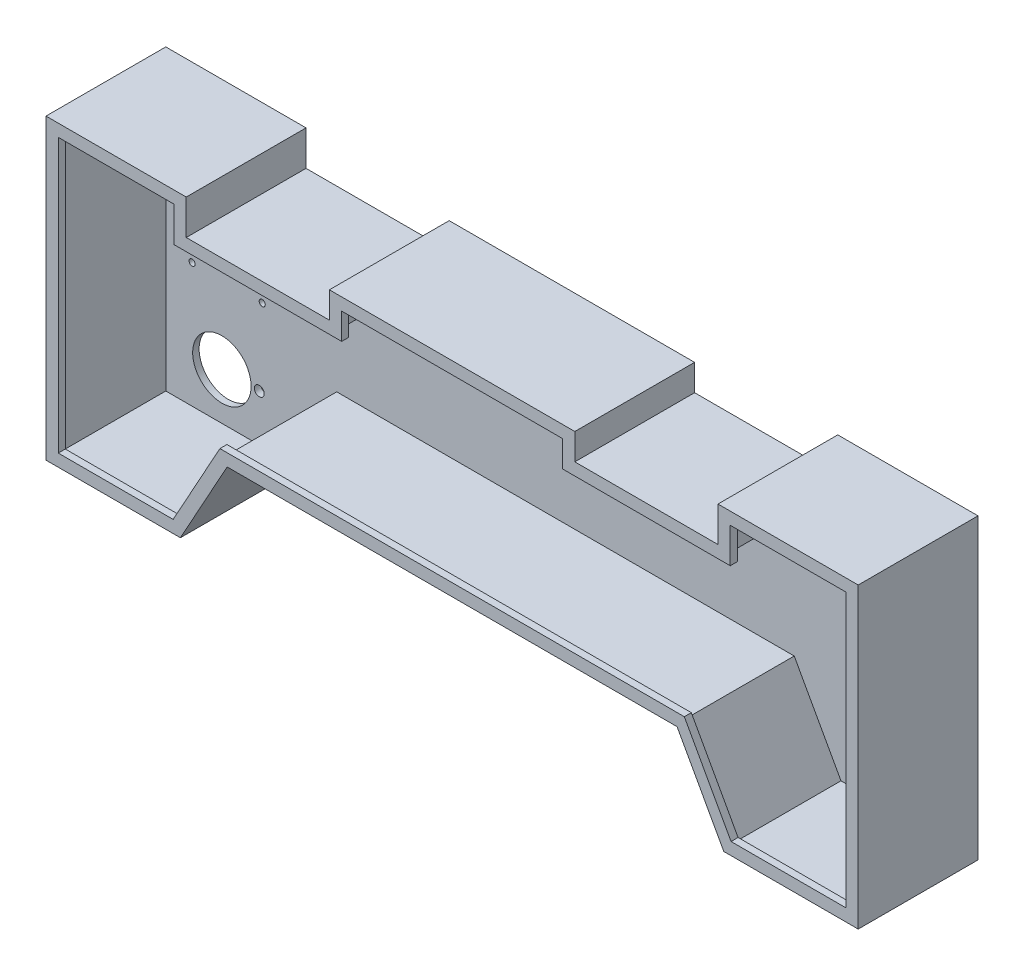
SolidWorks part; units mm, degrees
ref_plane "前视基准面" through (0, 0, 0) normal (0, 0, 1) x (1, 0, 0)
ref_plane "上视基准面" through (0, 0, 0) normal (0, 1, 0) x (1, 0, 0)
ref_plane "右视基准面" through (0, 0, 0) normal (1, 0, 0) x (0, 0, -1)
sketch "草图1" plane through (0, 0, 0) normal (0, 0, 1) x (1, 0, 0)
  line L0 (-61.0703, 36.5) -> (-37.0703, 36.5)
  line L1 (-37.0703, 36.5) -> (-37.0703, 30.5)
  line L2 (-37.0703, 30.5) -> (-12.5703, 30.5)
  line L3 (-12.5703, 30.5) -> (-12.5703, 35)
  line L4 (-12.5703, 35) -> (29.4297, 35)
  line L5 (29.4297, 35) -> (29.4297, 30.5)
  line L6 (29.4297, 30.5) -> (53.9297, 30.5)
  line L7 (53.9297, 30.5) -> (53.9297, 36.5)
  line L8 (53.9297, 36.5) -> (77.9297, 36.5)
  line L9 (77.9297, 36.5) -> (77.9297, -14.5)
  line L10 (77.9297, -14.5) -> (54.9297, -14.5)
  line L11 (-61.0703, 36.5) -> (-61.0703, -14.5)
  line L12 (-61.0703, -14.5) -> (-38.0703, -14.5)
  line L13 (8.4297, 98.6015) -> (8.4297, -28.6015) construction
  line L14 (-30.0703, 0) -> (46.9297, 0)
  line L15 (-30.0703, 0) -> (-38.0703, -14.5)
  line L16 (46.9297, 0) -> (54.9297, -14.5)
  point P17 (8.4297, 35)
  dimension "D1" = 24
  dimension "D2" = 6
  dimension "D3" = 24.5
  dimension "D4" = 4.5
  dimension "D5" = 42
  dimension "D6" = 4.5
  dimension "D7" = 24.5
  dimension "D8" = 6
  dimension "D9" = 24
  dimension "D10" = 51
  dimension "D11" = 51
  dimension "D12" = 77
  dimension "D13" = 38.5
  dimension "D14" = 30.5
  dimension "D15" = 23
  dimension "D16" = 23
extrude "凸台-拉伸1" add sketch "草图1" along normal blind 20.5
scale "缩放比例1" bodies to scale 106 scale about centroid uniform scaling yes scale factor 10
shell "抽壳1" thickness 11
ref_plane "基准面2" through (-457.5703, 231.1082, 112.75) normal (-1, 0, 0) x (0, 0, 1)
sketch "草图12" plane through (0, 0, 112.75) normal (0, 0, 1) x (1, 0, 0)
  line L32 (-665.5703, 221.1082) -> (-665.5703, -246.8918)
  line L33 (-665.5703, -246.8918) -> (-468.9682, -246.8918)
  line L34 (-468.9682, -246.8918) -> (-388.9682, -101.8918)
  line L35 (-388.9682, -101.8918) -> (405.8277, -101.8918)
  line L36 (405.8277, -101.8918) -> (485.8277, -246.8918)
  line L37 (485.8277, -246.8918) -> (682.4297, -246.8918)
  line L38 (682.4297, -246.8918) -> (682.4297, 221.1082)
  line L39 (682.4297, 221.1082) -> (484.4297, 221.1082)
  line L40 (484.4297, 221.1082) -> (484.4297, 161.1082)
  line L41 (484.4297, 161.1082) -> (197.4297, 161.1082)
  line L42 (197.4297, 161.1082) -> (197.4297, 206.1082)
  line L43 (197.4297, 206.1082) -> (-180.5703, 206.1082)
  line L44 (-180.5703, 206.1082) -> (-180.5703, 161.1082)
  line L45 (-180.5703, 161.1082) -> (-467.5703, 161.1082)
  line L46 (-467.5703, 161.1082) -> (-467.5703, 221.1082)
  line L47 (-467.5703, 221.1082) -> (-665.5703, 221.1082)
  line L48 (-665.5703, 221.1082) -> (-665.5703, -246.8918)
  line L49 (-665.5703, -246.8918) -> (-468.9682, -246.8918)
  line L50 (-468.9682, -246.8918) -> (-388.9682, -101.8918)
  line L51 (-388.9682, -101.8918) -> (405.8277, -101.8918)
  line L52 (405.8277, -101.8918) -> (485.8277, -246.8918)
  line L53 (485.8277, -246.8918) -> (682.4297, -246.8918)
  line L54 (682.4297, -246.8918) -> (682.4297, 221.1082)
  line L55 (682.4297, 221.1082) -> (484.4297, 221.1082)
  line L56 (484.4297, 221.1082) -> (484.4297, 161.1082)
  line L57 (484.4297, 161.1082) -> (197.4297, 161.1082)
  line L58 (197.4297, 161.1082) -> (197.4297, 206.1082)
  line L59 (197.4297, 206.1082) -> (-180.5703, 206.1082)
  line L60 (-180.5703, 206.1082) -> (-180.5703, 161.1082)
  line L61 (-180.5703, 161.1082) -> (-467.5703, 161.1082)
  line L62 (-467.5703, 161.1082) -> (-467.5703, 221.1082)
  line L63 (-467.5703, 221.1082) -> (-665.5703, 221.1082)
  line L64 (-675.5703, 231.1082) -> (-675.5703, -256.8918)
  line L65 (-675.5703, -256.8918) -> (-463.0644, -256.8918)
  line L66 (-463.0644, -256.8918) -> (-383.0644, -111.8918)
  line L67 (-383.0644, -111.8918) -> (399.9239, -111.8918)
  line L68 (399.9239, -111.8918) -> (479.9239, -256.8918)
  line L69 (479.9239, -256.8918) -> (692.4297, -256.8918)
  line L70 (692.4297, -256.8918) -> (692.4297, 231.1082)
  line L71 (692.4297, 231.1082) -> (474.4297, 231.1082)
  line L72 (474.4297, 231.1082) -> (474.4297, 171.1082)
  line L73 (474.4297, 171.1082) -> (207.4297, 171.1082)
  line L74 (207.4297, 171.1082) -> (207.4297, 216.1082)
  line L75 (207.4297, 216.1082) -> (-190.5703, 216.1082)
  line L76 (-190.5703, 216.1082) -> (-190.5703, 171.1082)
  line L77 (-190.5703, 171.1082) -> (-457.5703, 171.1082)
  line L78 (-457.5703, 171.1082) -> (-457.5703, 231.1082)
  line L79 (-457.5703, 231.1082) -> (-675.5703, 231.1082)
  line L80 (-675.5703, 231.1082) -> (-675.5703, -256.8918)
  line L81 (-675.5703, -256.8918) -> (-463.0644, -256.8918)
  line L82 (-463.0644, -256.8918) -> (-383.0644, -111.8918)
  line L83 (-383.0644, -111.8918) -> (399.9239, -111.8918)
  line L84 (399.9239, -111.8918) -> (479.9239, -256.8918)
  line L85 (479.9239, -256.8918) -> (692.4297, -256.8918)
  line L86 (692.4297, -256.8918) -> (692.4297, 231.1082)
  line L87 (692.4297, 231.1082) -> (474.4297, 231.1082)
  line L88 (474.4297, 231.1082) -> (474.4297, 171.1082)
  line L89 (474.4297, 171.1082) -> (207.4297, 171.1082)
  line L90 (207.4297, 171.1082) -> (207.4297, 216.1082)
  line L91 (207.4297, 216.1082) -> (-190.5703, 216.1082)
  line L92 (-190.5703, 216.1082) -> (-190.5703, 171.1082)
  line L93 (-190.5703, 171.1082) -> (-457.5703, 171.1082)
  line L94 (-457.5703, 171.1082) -> (-457.5703, 231.1082)
  line L95 (-457.5703, 231.1082) -> (-675.5703, 231.1082)
  dimension "D1" = 10
  dimension "D2" = 0
extrude "凸台-拉伸2" add sketch "草图12" against normal blind 12
sketch "草图22" plane through (0, 0, -81.25) normal (0, 0, 1) x (1, 0, 0)
  line L0 (-457.5703, 231.1082) -> (-675.5703, 231.1082) construction
  line L1 (-675.5703, 231.1082) -> (-675.5703, -256.8918) construction
  line L2 (-675.5703, -256.8918) -> (-463.0644, -256.8918) construction
  line L3 (692.4297, -256.8918) -> (692.4297, 231.1082) construction
  line L4 (692.4297, 231.1082) -> (474.4297, 231.1082) construction
  line L5 (479.9239, -256.8918) -> (692.4297, -256.8918) construction
  point P0 (-505.5703, 141.1082)
  point P2 (-630.5703, 36.1082)
  point P4 (-515.5703, -176.8918)
  point P6 (647.4297, 36.1082)
  point P8 (522.4297, 136.1082)
  point P10 (532.4297, -176.8918)
  dimension "D1" = 195
  dimension "D2" = 45
  dimension "D3" = 90
  dimension "D4" = 170
  dimension "D5" = 80
  dimension "D6" = 160
  dimension "D7" = 45
  dimension "D8" = 195
  dimension "D9" = 95
  dimension "D10" = 170
  dimension "D11" = 160
  dimension "D12" = 80
hole_wizard "Ø17.0 (17) 直径孔1" positions "草图22" profile "草图23" hole size "Ø17.0" standard "GB" end condition through all
sketch "草图23" plane through (-505.5703, 141.1082, -81.25) normal (1, 0, 0) x (0, -1, 0)
  line L0 (0, 0) -> (0, 11)
  line L1 (0, 11) -> (8.5, 11)
  line L2 (8.5, 11) -> (8.5, 0)
  line L5 (8.5, 0) -> (0, 0)
  line L11 (0, -6.35) -> (0, 107.95) construction
  dimension "通孔孔直径" = 17
  dimension "通孔孔深度" = 11
sketch "草图24" plane through (0, 0, -81.25) normal (0, 0, 1) x (1, 0, 0)
  line L0 (-457.5703, 231.1082) -> (-675.5703, 231.1082) construction
  line L1 (-675.5703, 231.1082) -> (-675.5703, -256.8918) construction
  line L3 (692.4297, 231.1082) -> (474.4297, 231.1082) construction
  line L4 (692.4297, -256.8918) -> (692.4297, 231.1082) construction
  point P0 (-630.5703, -43.8918)
  point P2 (-510.5703, -43.8918)
  point P4 (527.4297, -43.8918)
  point P6 (647.4297, -43.8918)
  dimension "D1" = 120
  dimension "D2" = 275
  dimension "D3" = 165
  dimension "D4" = 120
  dimension "D5" = 275
  dimension "D6" = 165
hole_wizard "M12x1.25 螺纹孔2" positions "草图24" profile "草图25" tap size "M12x1.25" standard "GB" end condition through all
sketch "草图25" plane through (-630.5703, -43.8918, -81.25) normal (1, 0, 0) x (0, -1, 0)
  line L0 (0, 0) -> (0, 11)
  line L1 (0, 11) -> (5.25, 11)
  line L2 (5.25, 11) -> (5.25, 0)
  line L5 (5.25, 0) -> (0, 0)
  line L11 (0, -6.35) -> (0, 107.95) construction
  dimension "通孔螺纹孔钻头直径" = 10.5
  dimension "通孔螺纹孔钻头深度" = 11
cosmetic thread "孔螺蚊线5" parameters "D2"=12
cosmetic thread "孔螺蚊线6" parameters "D2"=12
cosmetic thread "孔螺蚊线7" parameters "D2"=12
cosmetic thread "孔螺蚊线8" parameters "D2"=12
hole_wizard "Ø12.0mm 暗销孔1" positions "3D草图2" profile "草图26" hole size "Ø12.0" standard "GB" end condition through all
sketch3d "3D草图2"
  line L0 (-675.5703, 231.1082, -81.25) -> (-675.5703, -256.8918, -81.25) construction
  line L1 (692.4297, -256.8918, -81.25) -> (692.4297, 231.1082, -81.25) construction
  circle A0 centre (-510.5703, -43.8918, -81.25) radius 5.25 construction
  circle A1 centre (-630.5703, -43.8918, -81.25) radius 5.25 construction
  circle A2 centre (527.4297, -43.8918, -81.25) radius 5.25 construction
  circle A4 centre (647.4297, -43.8918, -81.25) radius 5.25 construction
  point P0 (-630.5703, 201.1082, -81.25)
  point P2 (-510.5703, 201.1082, -81.25)
  point P4 (527.4297, 201.1082, -81.25)
  point P6 (647.4297, 201.1082, -81.25)
  point P11 (-510.5703, -43.8918, -76)
  point P14 (-630.5703, -43.8918, -76)
  point P21 (527.4297, -43.8918, -76)
  point P27 (647.4297, -43.8918, -76)
  dimension "D1" = 120
  dimension "D2" = 245
  dimension "D3" = 245
  dimension "D4" = 165
  dimension "D5" = 120
  dimension "D6" = 165
  dimension "D7" = 245
  dimension "D8" = 245
sketch "草图26" plane through (-630.5703, 201.1082, -81.25) normal (1, 0, 0) x (0, -1, 0)
  line L0 (0, 0) -> (0, 11)
  line L1 (0, 11) -> (6, 11)
  line L2 (6, 11) -> (6, 0)
  line L5 (6, 0) -> (0, 0)
  line L11 (0, -6.35) -> (0, 107.95) construction
  dimension "通孔孔直径" = 12
  dimension "通孔孔深度" = 11
sketch "草图27" plane through (0, 0, -81.25) normal (0, 0, 1) x (1, 0, 0)
  circle A0 centre (572.4297, -176.8918) radius 50
  circle A1 centre (-579.5703, -176.8918) radius 50
  dimension "D1" = 100
  dimension "D2" = 100
extrude "切除-拉伸1" cut sketch "草图27" against normal up to surface (11 mm away) up to face at (-624.5703, 201.1082, -92.25)
